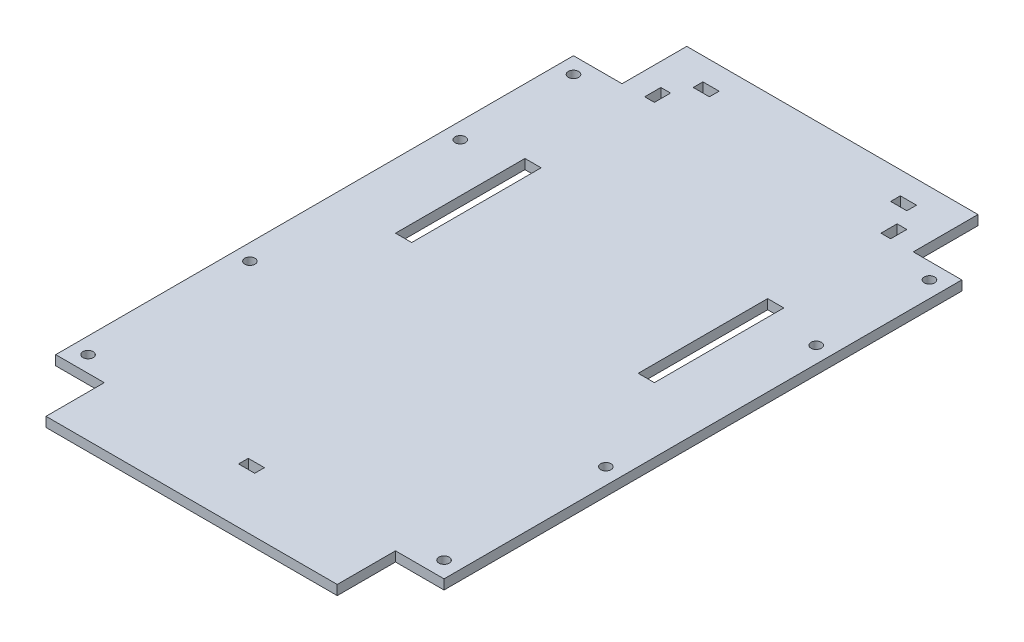
SolidWorks part; units mm, degrees
ref_plane "Front" through (0, 0, 0) normal (0, 0, 1) x (1, 0, 0)
ref_plane "Top" through (0, 0, 0) normal (0, 1, 0) x (1, 0, 0)
ref_plane "Right" through (0, 0, 0) normal (1, 0, 0) x (0, 0, -1)
sketch "孔位‘" plane through (0, 0, 0) normal (0, 1, 0) x (1, 0, 0)
  line L1 (0, 0) -> (110, 0)
  line L2 (0, 0) -> (0, 100)
  line L3 (0, 100) -> (110, 100)
  line L4 (110, 0) -> (110, 100)
  line L5 (-5, 105) -> (115, 105)
  line L6 (-5, 105) -> (-5, -5)
  line L7 (-5, -5) -> (115, -5)
  line L8 (115, 105) -> (115, -5)
  dimension "D1" = 100
  dimension "D2" = 110
  dimension "D3" = 120
  dimension "D4" = 110
  dimension "D5" = 5
  dimension "D6" = 5
sketch "草图2" plane through (0, 0, 0) normal (0, 1, 0) x (1, 0, 0)
  line L1 (-5, 105) -> (115, 105)
  line L2 (-5, 105) -> (-5, -5)
  line L3 (-5, -5) -> (115, -5)
  line L4 (115, 105) -> (115, -5)
  circle A0 centre (0, 100) radius 1.6
  circle A1 centre (110, 100) radius 1.6
  circle A2 centre (0, 0) radius 1.6
  circle A3 centre (110, 0) radius 1.6
extrude "凸台-拉伸1" add sketch "草图2" along normal blind 3
sketch "草图3" plane through (0, 3, 0) normal (0, 1, 0) x (1, 0, 0)
  line L0 (-5, 105) -> (115, 105) construction
  line L1 (20, 115) -> (90, 115)
  line L2 (20, 115) -> (20, -53)
  line L3 (20, -53) -> (90, -53)
  line L4 (90, 115) -> (90, -53)
  point P4 (55, 115)
  point P7 (55, 105)
  dimension "D1" = 70
  dimension "D2" = 168
  dimension "D3" = 0
  dimension "D4" = 10
sketch "草图4" plane through (0, 3, 0) normal (0, 1, 0) x (1, 0, 0)
  line L0 (20, 115) -> (20, -53) construction
  line L1 (10, 125) -> (100, 125)
  line L2 (10, 125) -> (10, -73)
  line L3 (10, -73) -> (100, -73)
  line L4 (100, 125) -> (100, -73)
  line L5 (20, 115) -> (90, 115) construction
  line L6 (20, -53) -> (90, -53) construction
  dimension "D1" = 90
  dimension "D2" = 10
  dimension "D3" = 10
  dimension "D4" = 20
extrude "凸台-拉伸2" add sketch "草图4" against normal blind 3
sketch "草图7" plane through (0, 3, 0) normal (0, 1, 0) x (1, 0, 0)
  line L0 (20, 115) -> (90, 115) construction
  line L1 (22, 115) -> (27, 115)
  line L2 (22, 115) -> (22, 118)
  line L3 (22, 118) -> (27, 118)
  line L4 (27, 115) -> (27, 118)
  line L5 (20, 115) -> (20, -53) construction
  line L7 (20, 110) -> (17, 110)
  line L8 (20, 110) -> (20, 105)
  line L9 (20, 105) -> (17, 105)
  line L10 (17, 110) -> (17, 105)
  dimension "D1" = 3
  dimension "D2" = 5
  dimension "D3" = 2
  dimension "D4" = 3
  dimension "D5" = 5
  dimension "D6" = 5
extrude "切除-拉伸1" cut sketch "草图7" against normal through all
ref_plane "基准面1" through (55, 0, 0) normal (-1, 0, 0) x (0, 0, 1)
mirror "镜向1" about plane through (55, 0, 0) normal (-1, 0, 0) of "切除-拉伸1"
sketch "草图8" plane through (0, 3, 0) normal (0, 1, 0) x (1, 0, 0)
  line L0 (20, -53) -> (90, -53) construction
  line L1 (52.5, -53) -> (57.5, -53)
  line L2 (52.5, -53) -> (52.5, -56)
  line L3 (52.5, -56) -> (57.5, -56)
  line L4 (57.5, -53) -> (57.5, -56)
  point P4 (55, -53)
  point P7 (55, -53)
  dimension "D1" = 5
  dimension "D2" = 3
  dimension "D3" = 0
  dimension "D4" = 0
extrude "切除-拉伸2" cut sketch "草图8" against normal through all
sketch "草图9" plane through (0, 3, 0) normal (0, 1, 0) x (1, 0, 0)
  line L0 (20, 115) -> (20, -53) construction
  line L1 (15, 70) -> (20, 70)
  line L2 (15, 70) -> (15, 30)
  line L3 (15, 30) -> (20, 30)
  line L4 (20, 70) -> (20, 30)
  line L5 (90, 115) -> (90, -53) construction
  line L6 (90, 70) -> (95, 70)
  line L7 (90, 70) -> (90, 30)
  line L8 (90, 30) -> (95, 30)
  line L9 (95, 70) -> (95, 30)
  line L10 (-5, 105) -> (-5, -5) construction
  line L11 (115, -5) -> (115, 105) construction
  point P12 (15, 50)
  point P15 (-5, 50)
  point P16 (95, 50)
  point P19 (115, 50)
  dimension "D1" = 5
  dimension "D2" = 40
  dimension "D3" = 0
  dimension "D4" = 5
  dimension "D5" = 40
  dimension "D6" = 0
extrude "切除-拉伸3" cut sketch "草图9" against normal through all
sketch "草图10" plane through (0, 3, 0) normal (0, 1, 0) x (1, 0, 0)
  line L1 (10, -5) -> (-5, -5)
  line L2 (10, -5) -> (10, -55)
  line L3 (10, -55) -> (-5, -55)
  line L4 (-5, -5) -> (-5, -55)
  line L5 (100, -5) -> (115, -5)
  line L6 (100, -5) -> (100, -55)
  line L7 (100, -55) -> (115, -55)
  line L8 (115, -5) -> (115, -55)
  dimension "D1" = 50
  dimension "D2" = 50
extrude "凸台-拉伸5" add sketch "草图10" against normal blind 3
sketch "草图11" plane through (0, 3, 0) normal (0, 1, 0) x (1, 0, 0)
  line L0 (-5, -55) -> (10, -55) construction
  circle A0 centre (0, -50) radius 1.6
  circle A1 centre (0, 65) radius 1.6
  circle A2 centre (110, -50) radius 1.6
  circle A3 centre (110, 65) radius 1.6
  dimension "D1" = 5
  dimension "D2" = 115
  dimension "D3" = 0
  dimension "D4" = 0
extrude "切除-拉伸4" cut sketch "草图11" against normal through all
